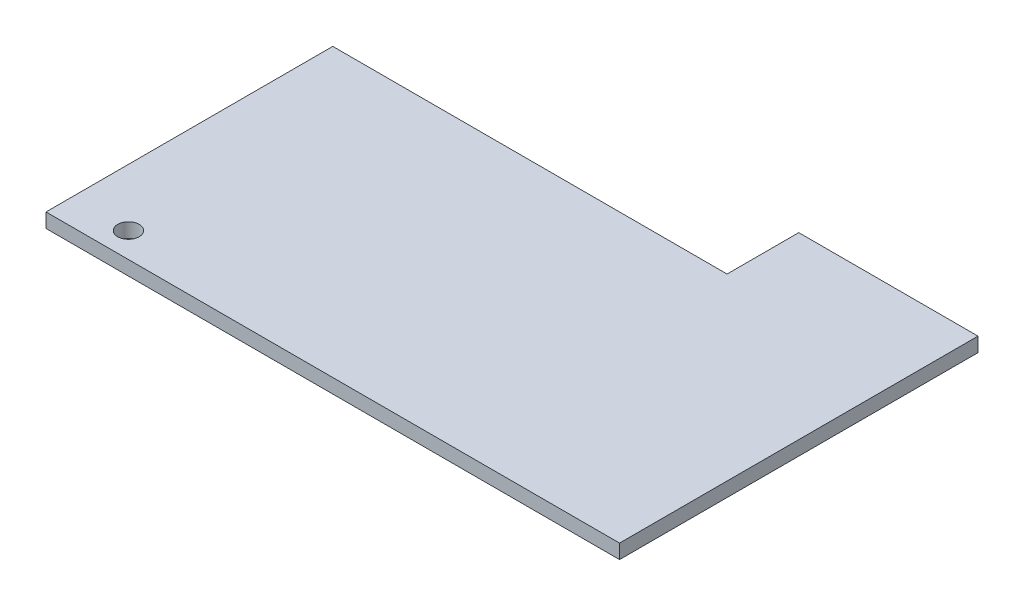
SolidWorks part; units mm, degrees
ref_plane "Front Plane" through (0, 0, 0) normal (0, 0, 1) x (1, 0, 0)
ref_plane "Top Plane" through (0, 0, 0) normal (0, 1, 0) x (1, 0, 0)
ref_plane "Right Plane" through (0, 0, 0) normal (1, 0, 0) x (0, 0, -1)
sketch "Sketch1" plane through (0, 0, 0) normal (0, 1, 0) x (1, 0, 0)
  line L1 (0, 0) -> (80, 0)
  line L2 (0, 0) -> (0, 50)
  line L3 (0, 50) -> (80, 50)
  line L4 (80, 0) -> (80, 50)
  dimension "D1" = 50
  dimension "D2" = 80
extrude "Boss-Extrude1" add sketch "Sketch1" along normal blind 2
sketch "Sketch2" plane through (0, 2, 0) normal (0, 1, 0) x (1, 0, 0)
  line L0 (0, 0) -> (80, 0) construction
  line L1 (0, 50) -> (0, 0) construction
  circle A0 centre (8, 3.5) radius 1.5
  dimension "D1" = 3
  dimension "D3" = 8
  dimension "D2" = 3.5
extrude "Cut-Extrude1" cut sketch "Sketch2" against normal blind 2
sketch "Sketch3" plane through (0, 2, 0) normal (0, 1, 0) x (1, 0, 0)
  line L0 (80, 50) -> (0, 50) construction
  line L1 (0, 50) -> (55, 50)
  line L2 (0, 50) -> (0, 40)
  line L3 (0, 40) -> (55, 40)
  line L4 (55, 50) -> (55, 40)
  dimension "D1" = 10
  dimension "D2" = 55
extrude "Cut-Extrude2" cut sketch "Sketch3" against normal through all
